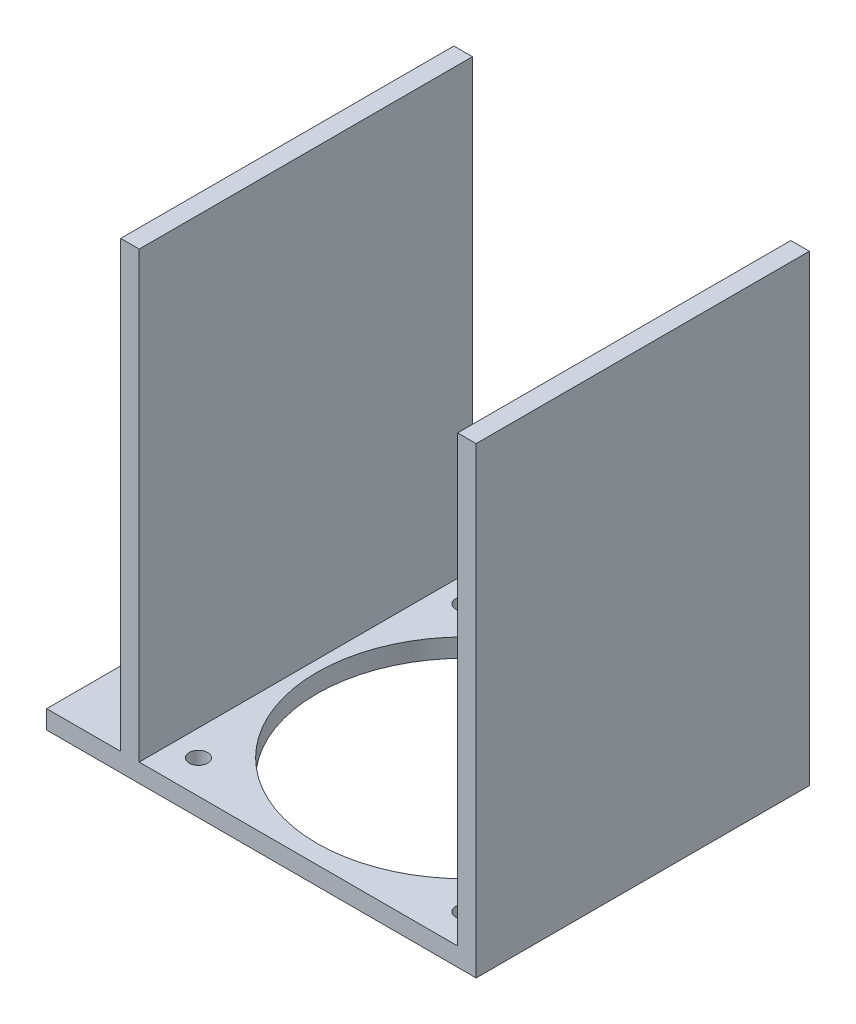
SolidWorks part; units mm, degrees
ref_plane "Front Plane" through (0, 0, 0) normal (0, 0, 1) x (1, 0, 0)
ref_plane "Top Plane" through (0, 0, 0) normal (0, 1, 0) x (1, 0, 0)
ref_plane "Right Plane" through (0, 0, 0) normal (1, 0, 0) x (0, 0, -1)
sketch "Sketch1" plane through (0, 0, 0) normal (0, 1, 0) x (1, 0, 0)
  line L1 (0, 0) -> (116, 0)
  line L2 (0, 0) -> (0, 90)
  line L3 (0, 90) -> (116, 90)
  line L4 (116, 0) -> (116, 90)
  line L5 (0, 0) -> (116, 90) construction
  line L6 (0, 90) -> (116, 0) construction
  point P4 (58, 45)
  dimension "D1" = 90
  dimension "D2" = 116
extrude "Boss-Extrude1" add sketch "Sketch1" along normal blind 5
sketch "Sketch2" plane through (0, 5, 0) normal (0, 1, 0) x (1, 0, 0)
  line L0 (116, 0) -> (116, 90) construction
  line L1 (116, 90) -> (111, 90)
  line L2 (116, 90) -> (116, 0)
  line L3 (116, 0) -> (111, 0)
  line L4 (111, 90) -> (111, 0)
  line L5 (116, 90) -> (111, 0) construction
  line L6 (116, 0) -> (111, 90) construction
  line L7 (0, 0) -> (116, 0) construction
  line L8 (116, 90) -> (0, 90) construction
  point P4 (113.5, 45)
  dimension "D1" = 5
extrude "Boss-Extrude2" add sketch "Sketch2" along normal blind 120
sketch "Sketch3" plane through (0, 0, 0) normal (0, -1, 0) x (1, 0, 0)
  circle A0 centre (68, -45) radius 40
  dimension "D1" = 80
extrude "Cut-Extrude1" cut sketch "Sketch3" against normal blind 15
sketch "Sketch4" plane through (0, 0, 0) normal (0, -1, 0) x (1, 0, 0)
  circle A0 centre (32, -9) radius 2.5
  circle A1 centre (104, -9) radius 2.5
  circle A2 centre (104, -81) radius 2.5
  circle A3 centre (32, -81) radius 2.5
extrude "Cut-Extrude2" cut sketch "Sketch4" against normal blind 15
sketch "Sketch5" plane through (0, 5, 0) normal (0, 1, 0) x (1, 0, 0)
  line L0 (111, 90) -> (0, 90) construction
  line L1 (20, 90) -> (25, 90)
  line L2 (20, 90) -> (20, 0)
  line L3 (20, 0) -> (25, 0)
  line L4 (25, 90) -> (25, 0)
  line L5 (20, 90) -> (25, 0) construction
  line L6 (20, 0) -> (25, 90) construction
  line L7 (0, 0) -> (111, 0) construction
  line L8 (0, 90) -> (0, 0) construction
  point P4 (22.5, 45)
  dimension "D1" = 5
  dimension "D2" = 20
extrude "Boss-Extrude3" add sketch "Sketch5" along normal blind 120
